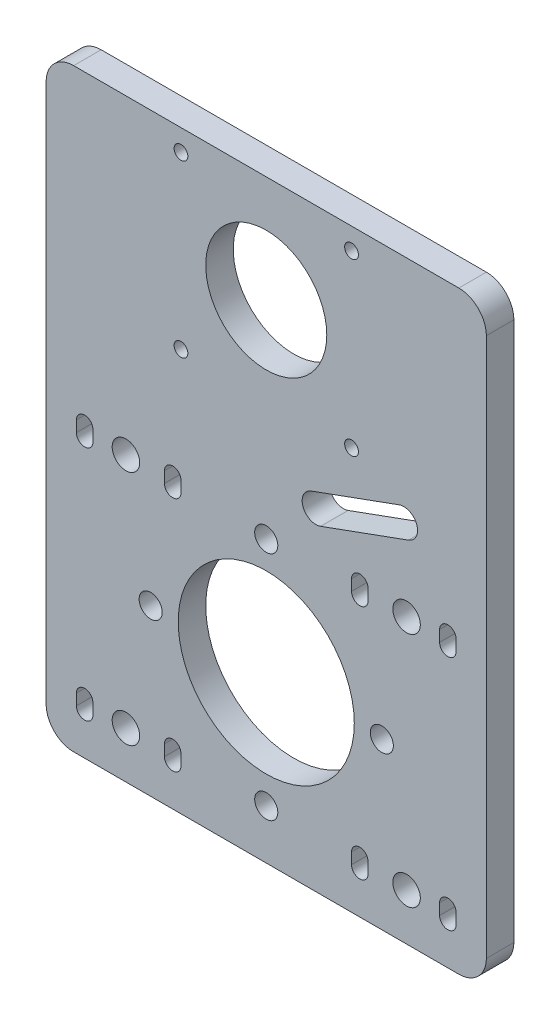
SolidWorks part; units mm, degrees
material "6061 Alloy"
ref_plane "Front Plane" through (0, 0, 0) normal (0, 0, 1) x (1, 0, 0)
ref_plane "Top Plane" through (0, 0, 0) normal (0, 1, 0) x (1, 0, 0)
ref_plane "Right Plane" through (0, 0, 0) normal (1, 0, 0) x (0, 0, -1)
sketch "Sketch1" plane through (0, 0, 0) normal (0, 0, 1) x (1, 0, 0)
  line L0 (33, -46.5) -> (33, -44.5) construction
  line L1 (-40, 54) -> (40, 54)
  line L2 (-40, 54) -> (-40, -54)
  line L3 (-40, -54) -> (40, -54)
  line L4 (40, 54) -> (40, -54)
  line L5 (0, -54) -> (0, 54) construction
  line L6 (-40, 0) -> (40, 0) construction
  line L7 (-21, -45) -> (21, -45)
  line L8 (-21, -45) -> (-21, -3)
  line L9 (-21, -3) -> (21, -3)
  line L10 (21, -45) -> (21, -3)
  line L11 (0, -3) -> (0, -45) construction
  line L12 (-21, -24) -> (21, -24) construction
  line L13 (-15.5, 19.1) -> (15.5, 19.1)
  line L14 (-15.5, 19.1) -> (-15.5, 50.1)
  line L15 (-15.5, 50.1) -> (15.5, 50.1)
  line L16 (15.5, 19.1) -> (15.5, 50.1)
  line L17 (0, 50.1) -> (0, 19.1) construction
  line L18 (-15.5, 34.6) -> (15.5, 34.6) construction
  line L21 (31.5, -46.5) -> (31.5, -44.5)
  line L24 (-33, -46.5) -> (-33, -44.5) construction
  line L27 (-31.5, -46.5) -> (-31.5, -44.5)
  line L30 (-34.5, -46.5) -> (-34.5, -44.5)
  line L33 (-17, -46.5) -> (-17, -44.5) construction
  line L36 (-15.5, -46.5) -> (-15.5, -44.5)
  line L39 (-18.5, -46.5) -> (-18.5, -44.5)
  line L42 (34.5, -46.5) -> (34.5, -44.5)
  line L43 (17, -46.5) -> (17, -44.5) construction
  line L44 (15.5, -46.5) -> (15.5, -44.5)
  line L45 (18.5, -46.5) -> (18.5, -44.5)
  line L46 (-33, -1.5) -> (-33, -3.5) construction
  line L47 (-31.5, -1.5) -> (-31.5, -3.5)
  line L48 (-34.5, -1.5) -> (-34.5, -3.5)
  line L49 (-17, -1.5) -> (-17, -3.5) construction
  line L50 (-15.5, -1.5) -> (-15.5, -3.5)
  line L51 (-18.5, -1.5) -> (-18.5, -3.5)
  line L52 (33, -1.5) -> (33, -3.5) construction
  line L53 (31.5, -1.5) -> (31.5, -3.5)
  line L54 (34.5, -1.5) -> (34.5, -3.5)
  line L55 (17, -1.5) -> (17, -3.5) construction
  line L56 (15.5, -1.5) -> (15.5, -3.5)
  line L57 (18.5, -1.5) -> (18.5, -3.5)
  line L58 (9.0252, 6.2857) -> (25, 12.1) construction
  line L59 (8.1702, 8.6349) -> (24.1449, 14.4492)
  line L60 (9.8803, 3.9364) -> (25.8551, 9.7508)
  circle A0 centre (0, -24) radius 16
  circle A1 centre (0, 34.6) radius 11
  circle A2 centre (21, -24) radius 2.1
  circle A3 centre (-21, -24) radius 2.1
  circle A4 centre (0, -3) radius 2.1
  circle A5 centre (0, -45) radius 2.1
  circle A6 centre (15.5, 50.1) radius 1.25
  circle A7 centre (15.5, 19.1) radius 1.25
  circle A8 centre (-15.5, 19.1) radius 1.25
  circle A9 centre (-15.5, 50.1) radius 1.25
  circle A10 centre (25.5, -45.5) radius 2.5
  arc A30 (31.5, -46.5) -> (34.5, -46.5) centre (33, -46.5) ccw
  arc A31 (34.5, -44.5) -> (31.5, -44.5) centre (33, -44.5) ccw
  arc A32 (15.5, -46.5) -> (18.5, -46.5) centre (17, -46.5) ccw
  arc A33 (18.5, -44.5) -> (15.5, -44.5) centre (17, -44.5) ccw
  arc A34 (-31.5, -46.5) -> (-34.5, -46.5) centre (-33, -46.5) cw
  arc A35 (-34.5, -44.5) -> (-31.5, -44.5) centre (-33, -44.5) cw
  arc A36 (-15.5, -46.5) -> (-18.5, -46.5) centre (-17, -46.5) cw
  arc A37 (-18.5, -44.5) -> (-15.5, -44.5) centre (-17, -44.5) cw
  circle A38 centre (-25.5, -45.5) radius 2.5
  arc A39 (-31.5, -1.5) -> (-34.5, -1.5) centre (-33, -1.5) ccw
  arc A40 (-34.5, -3.5) -> (-31.5, -3.5) centre (-33, -3.5) ccw
  circle A41 centre (-25.5, -2.5) radius 2.5
  arc A42 (-15.5, -1.5) -> (-18.5, -1.5) centre (-17, -1.5) ccw
  arc A43 (-18.5, -3.5) -> (-15.5, -3.5) centre (-17, -3.5) ccw
  arc A44 (31.5, -1.5) -> (34.5, -1.5) centre (33, -1.5) cw
  arc A45 (34.5, -3.5) -> (31.5, -3.5) centre (33, -3.5) cw
  circle A46 centre (25.5, -2.5) radius 2.5
  arc A47 (15.5, -1.5) -> (18.5, -1.5) centre (17, -1.5) cw
  arc A48 (18.5, -3.5) -> (15.5, -3.5) centre (17, -3.5) cw
  arc A51 (8.1702, 8.6349) -> (9.8803, 3.9364) centre (9.0252, 6.2857) ccw
  arc A52 (25.8551, 9.7508) -> (24.1449, 14.4492) centre (25, 12.1) ccw
  point P0 (0, 0)
  point P32 (33, -45.5)
  point P38 (17, -45.5)
  point P48 (-33, -45.5)
  point P55 (-17, -45.5)
  point P64 (-33, -2.5)
  point P73 (-17, -2.5)
  point P80 (33, -2.5)
  point P89 (17, -2.5)
  point P92 (17.0126, 9.1928)
  dimension "D6" = 22
  dimension "D7" = 2.5
  dimension "D10" = 32
  dimension "D11" = 4.2
  dimension "D15" = 5
  dimension "D16" = 8.5
  dimension "D19" = 1.5
  dimension "D20" = 2
  dimension "D18" = 1.5
  dimension "D22" = 17
  dimension "D23" = 2.5
  dimension "D1" = 108
  dimension "D2" = 80
  dimension "D3" = 58.6
  dimension "D4" = 15.5
  dimension "D5" = 15.5
  dimension "D8" = 21
  dimension "D9" = 21
  dimension "D12" = 30
  dimension "D13" = 14.5
  dimension "D14" = 7.5
  dimension "D17" = 2
  dimension "D21" = 8.5
  dimension "D24" = 15
  dimension "D25" = 70
  dimension "D26" = 7
extrude "Boss-Extrude1" add sketch "Sketch1" along normal mid plane 5 contours L4 L1 L2 L3 A9 L15 A6 L16 A7 L13 A8 L14 A5 L7 L8 A3 L9 A4 L10 A2 | A9 L14 A8 L13 A7 L16 A6 L15 A1 | A5 L7 L10 A2 L9 A4 L8 A3 A0
sketch "Sketch3" plane through (0, 0, 2.5) normal (0, 0, 1) x (1, 0, 0)
  line L0 (-42.2659, -24) -> (46.1995, -24) construction
fillet "Fillet1" radius 5 4 edges at (-40, -54, 0) (40, -54, 0) (-40, 54, 0) (40, 54, 0)
